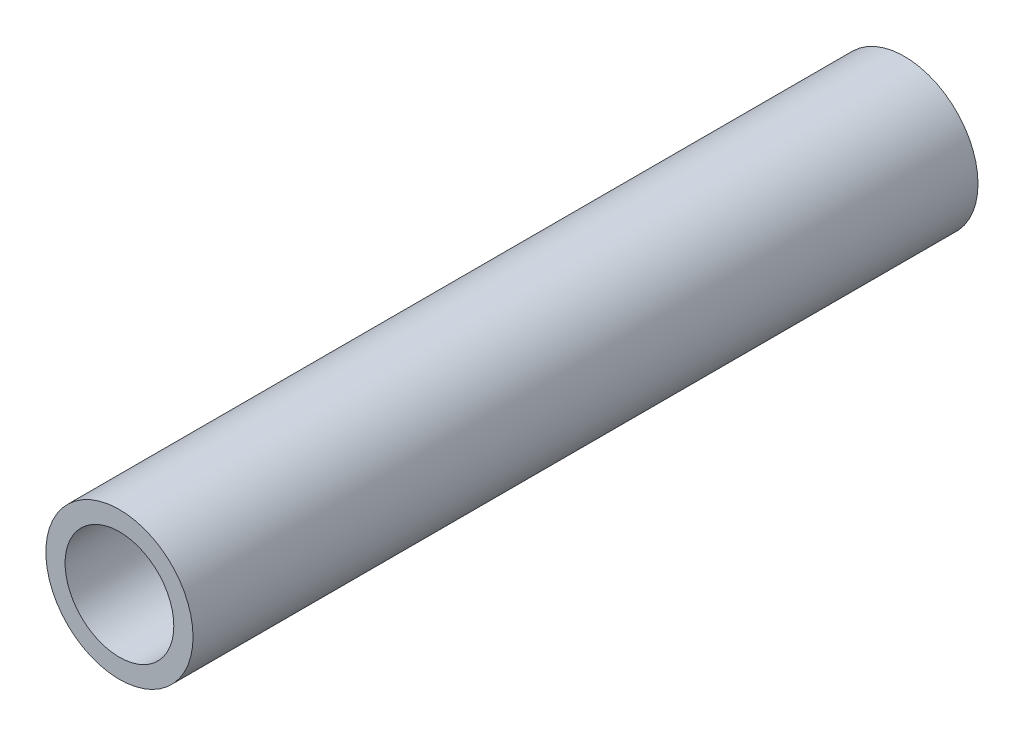
SolidWorks part; units mm, degrees
material "6061-T6 (SS)"
ref_plane "Front Plane" through (0, 0, 0) normal (0, 0, 1) x (1, 0, 0)
ref_plane "Top Plane" through (0, 0, 0) normal (0, 1, 0) x (1, 0, 0)
ref_plane "Right Plane" through (0, 0, 0) normal (1, 0, 0) x (0, 0, -1)
sketch "Sketch2" plane through (0, 0, 0) normal (0, 0, 1) x (1, 0, 0)
  circle A0 centre (0, 0) radius 4.7625
  circle A1 centre (0, 0) radius 3.5179
  dimension "D1" = 9.525
  dimension "D2" = 7.0358
extrude "Boss-Extrude1" add sketch "Sketch2" along normal blind 50.8
